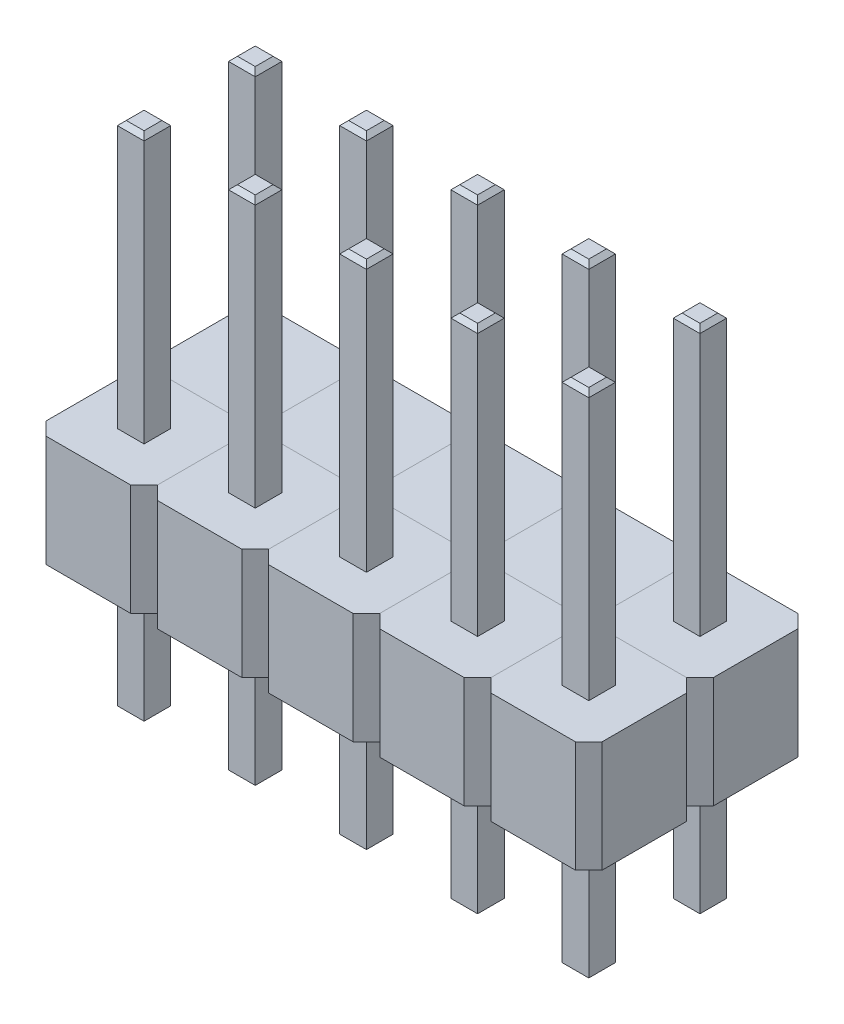
SolidWorks part; units mm, degrees
ref_plane "Front Plane" through (0, 0, 0) normal (0, 0, 1) x (1, 0, 0)
ref_plane "Top Plane" through (0, 0, 0) normal (0, 1, 0) x (1, 0, 0)
ref_plane "Right Plane" through (0, 0, 0) normal (1, 0, 0) x (0, 0, -1)
sketch "Sketch1" plane through (0, 0, 0) normal (0, 1, 0) x (1, 0, 0)
  line L0 (-32.85, -26.625) -> (32.85, -26.375) construction
  line L1 (-35.875, -29.25) -> (35.875, -29.25)
  line L2 (-35.875, -29.25) -> (-35.875, 29.25)
  line L3 (-35.875, 29.25) -> (35.875, 29.25)
  line L4 (35.875, -29.25) -> (35.875, 29.25)
  line L5 (-35.875, -29.25) -> (35.875, 29.25) construction
  line L6 (-35.875, 29.25) -> (35.875, -29.25) construction
  line L7 (32.85, -26.375) -> (32.75, 26.625) construction
  line L8 (32.75, 26.625) -> (-16.4, 26.625) construction
  circle A0 centre (-32.85, -26.625) radius 1.625
  circle A1 centre (32.85, -26.375) radius 1.625
  circle A2 centre (32.8075, -3.875) radius 1.625
  circle A3 centre (32.75, 26.625) radius 1.625
  circle A4 centre (-16.4, 26.625) radius 1.625
  point P0 (0, 0)
  point P16 (-32.85, -28.25)
  point P17 (-34.475, -26.625)
  point P18 (34.475, -26.375)
  point P19 (32.75, 28.25)
  point P20 (-18.025, 26.625)
  point P21 (-16.4, 28.25)
  point P22 (32.85, -28)
  point P23 (34.375, 26.625)
  point P24 (-31.225, -26.625)
  point P25 (31.225, -26.375)
  point P26 (32.85, -24.75)
  point P27 (32.8075, -5.5)
  point P28 (32.8075, -2.25)
  point P29 (32.75, 25)
  point P30 (31.125, 26.625)
  point P31 (-14.775, 26.625)
  dimension "D4" = 3.25
  dimension "D1" = 58.5
  dimension "D2" = 71.75
  dimension "D3" = 1.4
  dimension "D5" = 1
  dimension "D6" = 1.4
  dimension "D7" = 62.45
  dimension "D8" = 27.25
  dimension "D9" = 19.25
  dimension "D10" = 1.25
  dimension "D11" = 1
  dimension "D12" = 45.9
  dimension "D13" = 1
  dimension "D14" = 17.85
  dimension "D15" = 1.5
extrude "Boss-Extrude1" add sketch "Sketch1" along normal blind 1.6
sketch "Sketch7" plane through (0, 1.6, 0) normal (0, 1, 0) x (1, 0, 0)
  line L0 (-28.275, -25.85) -> (-27.975, -25.55)
  line L1 (-27.975, -25.55) -> (-26.075, -25.55)
  line L2 (-28.275, -25.85) -> (-28.275, -27.75)
  line L3 (-27.975, -28.05) -> (-26.075, -28.05)
  line L4 (-25.775, -25.85) -> (-25.775, -27.75)
  line L5 (-26.075, -25.55) -> (-25.775, -25.85)
  line L6 (-26.075, -28.05) -> (-25.775, -27.75)
  line L7 (-28.275, -27.75) -> (-27.975, -28.05)
  line L8 (-25.775, -25.55) -> (-28.275, -28.05) construction
  line L9 (-28.275, -25.55) -> (-25.775, -28.05) construction
  line L10 (-35.875, -29.25) -> (35.875, -29.25) construction
  line L11 (-35.875, 29.25) -> (-35.875, -29.25) construction
  point P0 (-28.275, -25.55)
  point P1 (-25.775, -28.05)
  point P2 (-28.275, -28.05)
  point P3 (-25.775, -25.55)
  point P16 (-27.025, -26.8)
  dimension "D1" = 2.5
  dimension "D2" = 1.2
  dimension "D7" = 7.6
extrude "Boss-Extrude5" add sketch "Sketch7" along normal blind 2.5 separate body
sketch "Sketch8" plane through (0, 4.1, 0) normal (0, 1, 0) x (1, 0, 0)
  line L0 (-28.275, -25.55) -> (-25.775, -28.05) construction
  line L1 (-27.325, -26.5) -> (-26.725, -26.5)
  line L2 (-27.325, -26.5) -> (-27.325, -27.1)
  line L3 (-27.325, -27.1) -> (-26.725, -27.1)
  line L4 (-26.725, -26.5) -> (-26.725, -27.1)
  line L5 (-27.325, -26.5) -> (-26.725, -27.1) construction
  line L6 (-27.325, -27.1) -> (-26.725, -26.5) construction
  point P0 (-27.025, -26.8)
  dimension "D1" = 0.6
extrude "Boss-Extrude6" add sketch "Sketch8" along normal blind 6 and the other way blind 5.5 separate body
chamfer "Фаска1" distance 0.1 angle 45 8 edges at (-27.025, 10.1, 27.1) (-27.325, 10.1, 26.8) (-27.025, 10.1, 26.5) (-26.725, 10.1, 26.8) (-27.025, -1.4, 26.5) (-27.325, -1.4, 26.8) (-27.025, -1.4, 27.1) (-26.725, -1.4, 26.8)
pattern_linear "LPattern1" count 5 spacing 2.5 along (1, 0, 0) count 2 spacing 2.5 along (0, 0, -1) of bodies 106 107
delete or keep bodies "Тело-Удалить/Сохранить 1" type delete bodies bodies 101
